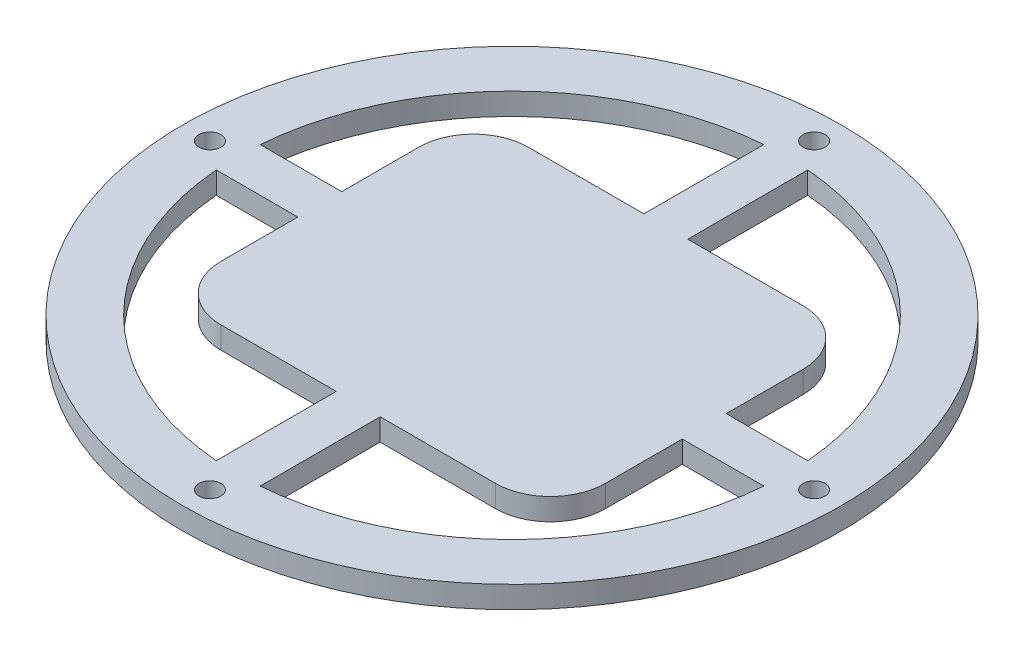
SolidWorks part; units mm, degrees
ref_plane "Front Plane" through (0, 0, 0) normal (0, 0, 1) x (1, 0, 0)
ref_plane "Top Plane" through (0, 0, 0) normal (0, 1, 0) x (1, 0, 0)
ref_plane "Right Plane" through (0, 0, 0) normal (1, 0, 0) x (0, 0, -1)
sketch "Sketch1" plane through (0, 0, 0) normal (0, 1, 0) x (1, 0, 0)
  circle A0 centre (0, 0) radius 30
  circle A1 centre (0, 0) radius 25
extrude "Boss-Extrude1" add sketch "Sketch1" along normal blind 2
sketch "Sketch2" plane through (0, 2, 0) normal (0, 1, 0) x (1, 0, 0)
  line L0 (0, 0) -> (0, 27.5)
  line L1 (0, 0) -> (0, -27.5)
  line L2 (0, 0) -> (27.5, 0)
  line L3 (0, 0) -> (-27.5, 0)
  circle A0 centre (0, 27.5) radius 1
  circle A1 centre (27.5, 0) radius 1
  circle A2 centre (0, -27.5) radius 1
  circle A3 centre (-27.5, 0) radius 1
extrude "Cut-Extrude1" cut sketch "Sketch2" against normal blind 2 contours A0 | A1 | A2 | A3
sketch "Sketch3" plane through (0, 0, 0) normal (0, 1, 0) x (1, 0, 0)
  line L0 (0, 0) -> (0, 12)
  line L1 (0, 0) -> (0, -12)
  line L2 (0, 0) -> (15.5, 0)
  line L3 (0, 0) -> (-15.5, 0)
  line L4 (2, 14) -> (17.5, 14)
  line L5 (17.5, 14) -> (17.5, 2)
  line L6 (17.5, -14) -> (2, -14)
  line L7 (-17.5, -14) -> (-17.5, -2)
  line L8 (-17.5, 14) -> (-2, 14)
  line L11 (17.5, -2) -> (17.5, -14)
  line L12 (-17.5, 2) -> (-17.5, 14)
  line L13 (-2, -14) -> (-17.5, -14)
  line L22 (-2, 14) -> (-2, 24.9199)
  line L23 (2, 14) -> (2, 24.9199)
  line L24 (17.5, 2) -> (24.9199, 2)
  line L25 (17.5, -2) -> (24.9199, -2)
  line L26 (2, -14) -> (2, -24.9199)
  line L27 (-2, -14) -> (-2, -24.9199)
  line L28 (-17.5, 2) -> (-24.9199, 2)
  line L29 (-17.5, -2) -> (-24.9199, -2)
  arc A0 (2, 24.9199) -> (-2, 24.9199) centre (0, 0) ccw
  arc A1 (24.9199, -2) -> (24.9199, 2) centre (0, 0) ccw
  arc A2 (-2, -24.9199) -> (2, -24.9199) centre (0, 0) ccw
  arc A3 (-24.9199, 2) -> (-24.9199, -2) centre (0, 0) ccw
extrude "Boss-Extrude2" add sketch "Sketch3" along normal blind 2
fillet "Fillet1" radius 5 4 edges at (-17.5, 1, -14) (-17.5, 1, 14) (17.5, 1, -14) (17.5, 1, 14)
